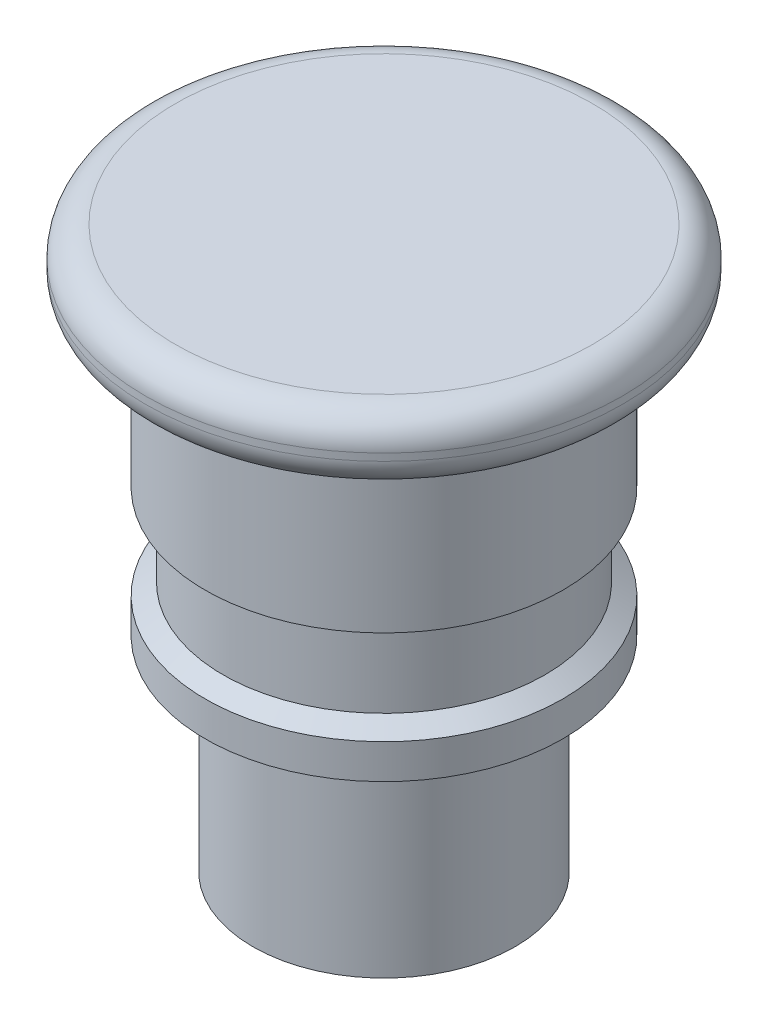
SolidWorks part; units mm, degrees
ref_plane "Front Plane" through (0, 0, 0) normal (0, 0, 1) x (1, 0, 0)
ref_plane "Top Plane" through (0, 0, 0) normal (0, 1, 0) x (1, 0, 0)
ref_plane "Right Plane" through (0, 0, 0) normal (1, 0, 0) x (0, 0, -1)
sketch "Sketch1" plane through (0, 0, 0) normal (0, 0, 1) x (1, 0, 0)
  line L0 (0, 11.8461) -> (0, -9.6529) construction
  line L1 (0, 29.9) -> (20, 29.9)
  line L2 (20, 29.9) -> (20, 24.3)
  line L3 (20, 24.3) -> (15, 24.3)
  line L4 (15, 24.3) -> (15, 10.8)
  line L5 (15, 10.8) -> (13.5, 10.8)
  line L6 (13.5, 10.8) -> (13.5, 3.9)
  line L7 (13.5, 3.9) -> (15, 2.9)
  line L8 (15, 2.9) -> (15, 0)
  line L9 (15, 0) -> (11, 0)
  line L10 (11, 0) -> (11, -17.1)
  line L11 (11, -17.1) -> (0, -17.1)
  line L12 (0, -17.1) -> (0, 29.9)
  line L13 (0, 0) -> (11, 0) construction
  dimension "D1" = 20
  dimension "D2" = 11
  dimension "D3" = 15
  dimension "D4" = 13.5
  dimension "D5" = 15
  dimension "D6" = 5.6
  dimension "D7" = 6.9
  dimension "D8" = 2.9
  dimension "D9" = 1
  dimension "D10" = 47
  dimension "D11" = 13.5
revolve "Revolve1" add sketch "Sketch1" angle 360 about L0
fillet "Fillet1" radius 2.5 2 edges at (-20, 24.3, 0) (-20, 29.9, 0)
